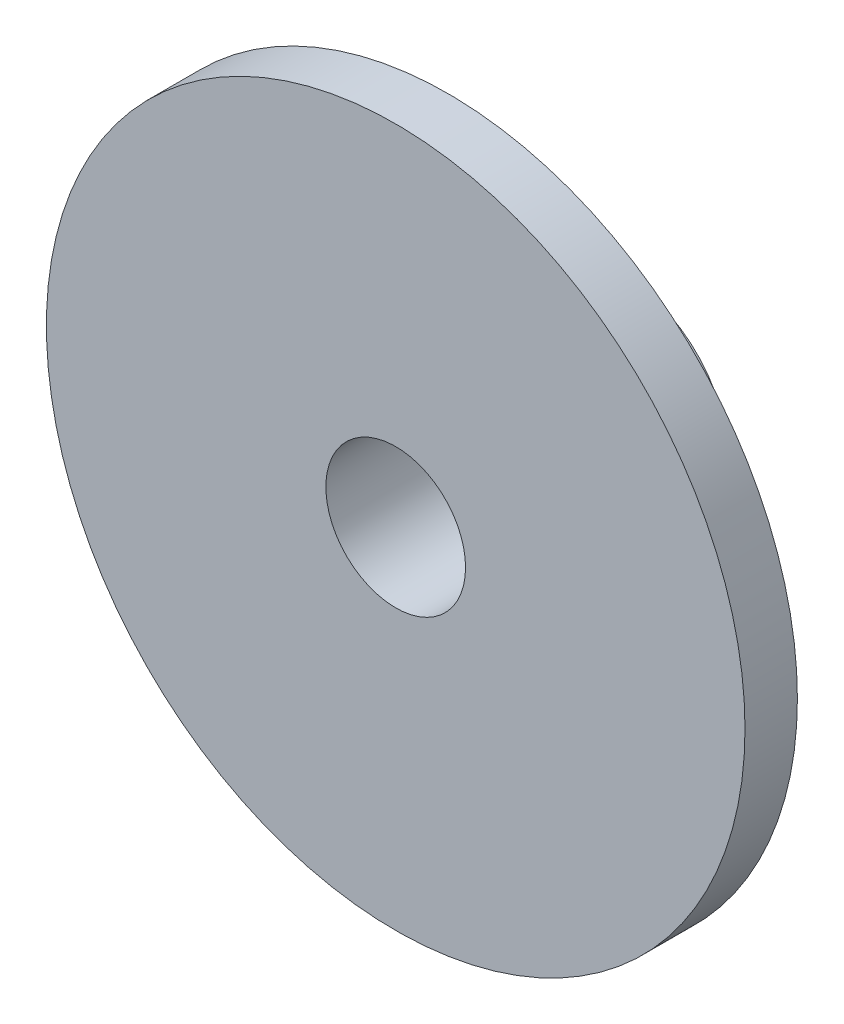
SolidWorks part; units mm, degrees
material "Brass"
ref_plane "Front Plane" through (0, 0, 0) normal (0, 0, 1) x (1, 0, 0)
ref_plane "Top Plane" through (0, 0, 0) normal (0, 1, 0) x (1, 0, 0)
ref_plane "Right Plane" through (0, 0, 0) normal (1, 0, 0) x (0, 0, -1)
sketch "Sketch1" plane through (0, 0, 0) normal (1, 0, 0) x (0, 0, -1)
  line L0 (0, 4) -> (13, 4)
  line L1 (13, 4) -> (13, 6)
  line L2 (13, 6) -> (3, 6)
  line L3 (3, 6) -> (3, 20)
  line L4 (3, 20) -> (0, 20)
  line L5 (0, 20) -> (0, 4)
  line L6 (0, 0) -> (24.2017, 0) construction
  dimension "D1" = 3
  dimension "D2" = 4
  dimension "D3" = 2
  dimension "D4" = 14
  dimension "D5" = 10
revolve "Revolve1" add sketch "Sketch1" angle 360 about L6
